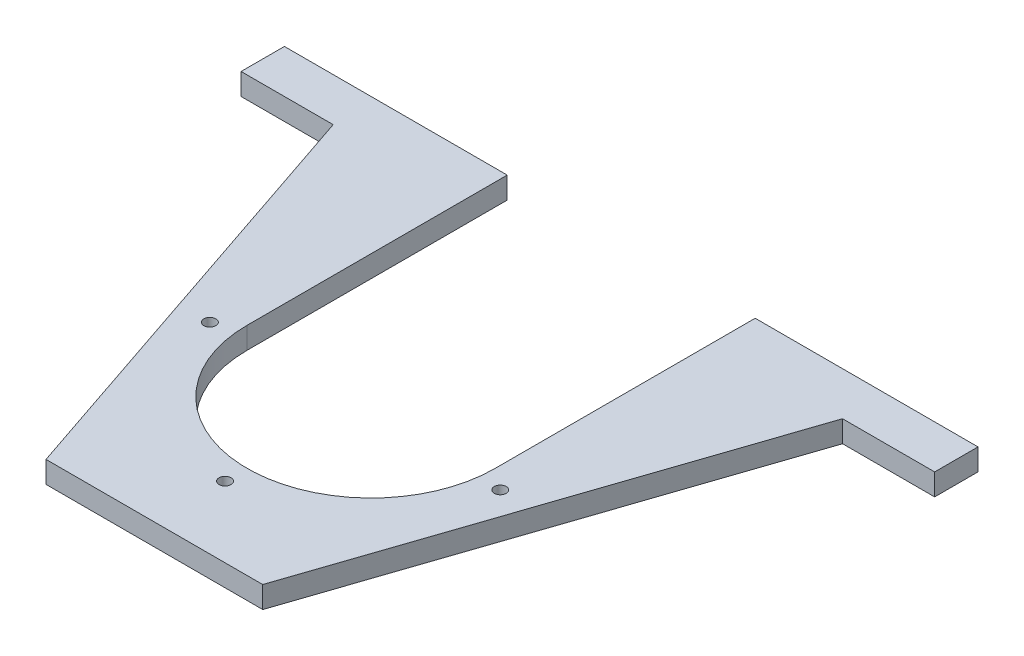
SolidWorks part; units mm, degrees
material "Pin"
ref_plane "Front" through (0, 0, 0) normal (0, 0, 1) x (1, 0, 0)
ref_plane "Top" through (0, 0, 0) normal (0, 1, 0) x (1, 0, 0)
ref_plane "Right" through (0, 0, 0) normal (1, 0, 0) x (0, 0, -1)
sketch "Esquisse1" plane through (0, 0, 0) normal (0, 1, 0) x (1, 0, 0)
  line L2 (-101.6, 139.7) -> (-101.6, 127)
  line L3 (-101.6, 127) -> (-74.6125, 127)
  line L4 (-74.6125, 127) -> (-31.75, 0)
  line L10 (0, 0) -> (0, 160.2728) construction
  line L12 (74.6125, 127) -> (31.75, 0)
  line L13 (101.6, 127) -> (74.6125, 127)
  line L14 (101.6, 139.7) -> (101.6, 127)
  line L18 (-101.6, 139.7) -> (101.6, 139.7)
  line L19 (-31.75, 0) -> (31.75, 0)
  point P2 (0, 0)
  point P6 (-88.1063, 127)
  dimension "D1" = 12.7
  dimension "D2" = 101.6
  dimension "D3" = 63.5
  dimension "D5" = 127
  dimension "D8" = 26.9875
extrude "Boss.-Extru.1" add sketch "Esquisse1" along normal blind 6.35
sketch "Esquisse3" plane through (0, 6.35, 0) normal (0, 1, 0) x (1, 0, 0)
  line L1 (-31.75, 0) -> (31.75, 0) construction
  circle A0 centre (0, 63.5) radius 36.322
  dimension "D1" = 72.644
  dimension "D2" = 63.5
extrude "Enlèv. mat.-Extru.2" cut sketch "Esquisse3" against normal through all
sketch "Esquisse4" plane through (0, 6.35, 0) normal (0, 1, 0) x (1, 0, 0)
  line L1 (65.4949, 139.7) -> (23.1087, 139.7)
  line L3 (61.2087, 127) -> (23.1087, 127)
  line L4 (23.1087, 139.7) -> (23.1087, 127)
  line L5 (101.6, 139.7) -> (-101.6, 139.7) construction
  line L6 (61.2087, 127) -> (65.4949, 139.7)
  line L7 (31.75, 0) -> (74.6125, 127) construction
  dimension "D1" = 12.7
  dimension "D2" = 38.1
  dimension "D3" = 12.7
extrude "Enlèv. mat.-Extru.3" [suppressed] cut sketch "Esquisse4" against normal through all
sketch "Esquisse5" plane through (0, 6.35, 0) normal (0, 1, 0) x (1, 0, 0)
  line L0 (0, 123.444) -> (0, 132.8849)
  line L1 (0, 132.8849) -> (3.175, 132.8849)
  line L2 (3.175, 132.8849) -> (3.175, 123.3599)
  line L3 (3.175, 123.3599) -> (0, 123.444)
  line L4 (14.8109, 121.7492) -> (11.7133, 122.4512)
  line L5 (11.7133, 122.4512) -> (13.5551, 131.7106)
  line L6 (13.5551, 131.7106) -> (16.6691, 131.0912)
  line L7 (16.6691, 131.0912) -> (14.8109, 121.7492)
  line L8 (25.909, 117.8995) -> (23.0079, 119.1923)
  line L9 (23.0079, 119.1923) -> (26.6207, 127.9145)
  line L10 (26.6207, 127.9145) -> (29.5541, 126.6995)
  line L11 (29.5541, 126.6995) -> (25.909, 117.8995)
  line L12 (36.0428, 111.9587) -> (33.4496, 113.7926)
  line L13 (33.4496, 113.7926) -> (38.6947, 121.6423)
  line L14 (38.6947, 121.6423) -> (41.3346, 119.8784)
  line L15 (41.3346, 119.8784) -> (36.0428, 111.9587)
  line L16 (44.8229, 104.1549) -> (42.6373, 106.4595)
  line L17 (42.6373, 106.4595) -> (49.313, 113.1352)
  line L18 (49.313, 113.1352) -> (51.5581, 110.8901)
  line L19 (51.5581, 110.8901) -> (44.8229, 104.1549)
  line L20 (51.9118, 94.7882) -> (50.2179, 97.4749)
  line L21 (50.2179, 97.4749) -> (58.0677, 102.72)
  line L22 (58.0677, 102.72) -> (59.8316, 100.08)
  line L23 (59.8316, 100.08) -> (51.9118, 94.7882)
  line L108 (-47.6582, 98.7102) -> (-49.4921, 96.117)
  line L109 (-49.4921, 96.117) -> (-57.3419, 101.3621)
  line L110 (-57.3419, 101.3621) -> (-55.5779, 104.002)
  line L111 (-55.5779, 104.002) -> (-47.6582, 98.7102)
  line L112 (-39.8544, 107.4903) -> (-42.159, 105.3047)
  line L113 (-42.159, 105.3047) -> (-48.8347, 111.9804)
  line L114 (-48.8347, 111.9804) -> (-46.5896, 114.2255)
  line L115 (-46.5896, 114.2255) -> (-39.8544, 107.4903)
  line L116 (-30.4878, 114.5792) -> (-33.1744, 112.8853)
  line L117 (-33.1744, 112.8853) -> (-38.4195, 120.735)
  line L118 (-38.4195, 120.735) -> (-35.7796, 122.499)
  line L119 (-35.7796, 122.499) -> (-30.4878, 114.5792)
  line L120 (-19.9181, 119.7046) -> (-22.8836, 118.5673)
  line L121 (-22.8836, 118.5673) -> (-26.4964, 127.2895)
  line L122 (-26.4964, 127.2895) -> (-23.5631, 128.5046)
  line L123 (-23.5631, 128.5046) -> (-19.9181, 119.7046)
  line L124 (-8.5515, 122.6695) -> (-11.6819, 122.1326)
  line L125 (-11.6819, 122.1326) -> (-13.5238, 131.392)
  line L126 (-13.5238, 131.392) -> (-10.4098, 132.0114)
  line L127 (-10.4098, 132.0114) -> (-8.5515, 122.6695)
  line L128 (57.0372, 84.2185) -> (55.8999, 87.184) [skipped]
  line L129 (55.8999, 87.184) -> (64.6222, 90.7969) [skipped]
  line L130 (64.6222, 90.7969) -> (65.8372, 87.8636) [skipped]
  line L131 (65.8372, 87.8636) -> (57.0372, 84.2185) [skipped]
  line L132 (60.0021, 72.852) -> (59.4652, 75.9824) [skipped]
  line L133 (59.4652, 75.9824) -> (68.7247, 77.8242) [skipped]
  line L134 (68.7247, 77.8242) -> (69.3441, 74.7102) [skipped]
  line L135 (69.3441, 74.7102) -> (60.0021, 72.852) [skipped]
  line L136 (60.6925, 61.1255) -> (60.7766, 64.3005) [skipped]
  line L137 (60.7766, 64.3005) -> (70.2175, 64.3005) [skipped]
  line L138 (70.2175, 64.3005) -> (70.2175, 61.1255) [skipped]
  line L139 (70.2175, 61.1255) -> (60.6925, 61.1255) [skipped]
  line L140 (59.0819, 49.4896) -> (59.7838, 52.5872) [skipped]
  line L141 (59.7838, 52.5872) -> (69.0433, 50.7453) [skipped]
  line L142 (69.0433, 50.7453) -> (68.4238, 47.6313) [skipped]
  line L143 (68.4238, 47.6313) -> (59.0819, 49.4896) [skipped]
  line L144 (55.2321, 38.3915) -> (56.5249, 41.2926) [skipped]
  line L145 (56.5249, 41.2926) -> (65.2471, 37.6797) [skipped]
  line L146 (65.2471, 37.6797) -> (64.0321, 34.7464) [skipped]
  line L147 (64.0321, 34.7464) -> (55.2321, 38.3915) [skipped]
  line L148 (49.2913, 28.2577) -> (51.1252, 30.8508) [skipped]
  line L149 (51.1252, 30.8508) -> (58.975, 25.6058) [skipped]
  line L150 (58.975, 25.6058) -> (57.211, 22.9659) [skipped]
  line L151 (57.211, 22.9659) -> (49.2913, 28.2577) [skipped]
  line L152 (41.4875, 19.4776) -> (43.7921, 21.6631) [skipped]
  line L153 (43.7921, 21.6631) -> (50.4678, 14.9875) [skipped]
  line L154 (50.4678, 14.9875) -> (48.2227, 12.7424) [skipped]
  line L155 (48.2227, 12.7424) -> (41.4875, 19.4776) [skipped]
  line L156 (32.1208, 12.3886) -> (34.8075, 14.0826) [skipped]
  line L157 (34.8075, 14.0826) -> (40.0526, 6.2328) [skipped]
  line L158 (40.0526, 6.2328) -> (37.4127, 4.4689) [skipped]
  line L159 (37.4127, 4.4689) -> (32.1208, 12.3886) [skipped]
  line L160 (21.5511, 7.2633) -> (24.5167, 8.4005) [skipped]
  line L161 (24.5167, 8.4005) -> (28.1295, -0.3217) [skipped]
  line L162 (28.1295, -0.3217) -> (25.1962, -1.5367) [skipped]
  line L163 (25.1962, -1.5367) -> (21.5511, 7.2633) [skipped]
  line L164 (10.1846, 4.2984) -> (13.315, 4.8353) [skipped]
  line L165 (-1.5419, 3.608) -> (1.6331, 3.5239) [skipped]
  line L166 (-13.1778, 5.2186) -> (-10.0802, 4.5167) [skipped]
  line L167 (-24.2759, 9.0683) -> (-21.3748, 7.7756) [skipped]
  line L168 (-21.3748, 7.7756) -> (-24.9876, -0.9466) [skipped]
  line L169 (-24.9876, -0.9466) -> (-27.921, 0.2684) [skipped]
  line L170 (-27.921, 0.2684) -> (-24.2759, 9.0683) [skipped]
  line L171 (-34.4097, 15.0092) -> (-31.8165, 13.1753) [skipped]
  line L172 (-31.8165, 13.1753) -> (-37.0616, 5.3255) [skipped]
  line L173 (-37.0616, 5.3255) -> (-39.7015, 7.0895) [skipped]
  line L174 (-39.7015, 7.0895) -> (-34.4097, 15.0092) [skipped]
  line L175 (-43.1898, 22.8129) -> (-41.0042, 20.5084) [skipped]
  line L176 (-41.0042, 20.5084) -> (-47.6799, 13.8327) [skipped]
  line L177 (-47.6799, 13.8327) -> (-49.925, 16.0777) [skipped]
  line L178 (-49.925, 16.0777) -> (-43.1898, 22.8129) [skipped]
  line L179 (-50.2787, 32.1796) -> (-48.5848, 29.493) [skipped]
  line L180 (-48.5848, 29.493) -> (-56.4346, 24.2479) [skipped]
  line L181 (-56.4346, 24.2479) -> (-58.1985, 26.8878) [skipped]
  line L182 (-58.1985, 26.8878) -> (-50.2787, 32.1796) [skipped]
  line L183 (-55.4041, 42.7493) -> (-54.2669, 39.7838) [skipped]
  line L184 (-54.2669, 39.7838) -> (-62.9891, 36.171) [skipped]
  line L185 (-62.9891, 36.171) -> (-64.2041, 39.1043) [skipped]
  line L186 (-64.2041, 39.1043) -> (-55.4041, 42.7493) [skipped]
  line L187 (-58.369, 54.1159) -> (-57.8321, 50.9854) [skipped]
  line L188 (-57.8321, 50.9854) -> (-67.0916, 49.1436) [skipped]
  line L189 (-67.0916, 49.1436) -> (-67.711, 52.2576) [skipped]
  line L190 (-67.711, 52.2576) -> (-58.369, 54.1159) [skipped]
  line L191 (-59.0594, 65.8424) -> (-59.1435, 62.6674) [skipped]
  line L192 (-59.1435, 62.6674) -> (-68.5844, 62.6674) [skipped]
  line L193 (-68.5844, 62.6674) -> (-68.5844, 65.8424) [skipped]
  line L194 (-68.5844, 65.8424) -> (-59.0594, 65.8424) [skipped]
  line L195 (-57.4488, 77.4783) -> (-58.1507, 74.3807) [skipped]
  line L196 (-58.1507, 74.3807) -> (-67.4102, 76.2225) [skipped]
  line L197 (-67.4102, 76.2225) -> (-66.7907, 79.3365) [skipped]
  line L198 (-66.7907, 79.3365) -> (-57.4488, 77.4783) [skipped]
  line L199 (-53.5991, 88.5764) -> (-54.8918, 85.6753) [skipped]
  line L200 (-54.8918, 85.6753) -> (-63.614, 89.2881) [skipped]
  line L201 (-63.614, 89.2881) -> (-62.399, 92.2214) [skipped]
  line L202 (-62.399, 92.2214) -> (-53.5991, 88.5764) [skipped]
  line L203 (13.315, 4.8353) -> (15.1569, -4.4242) [skipped]
  line L204 (15.1569, -4.4242) -> (12.0429, -5.0436) [skipped]
  line L205 (12.0429, -5.0436) -> (10.1846, 4.2984) [skipped]
  line L206 (1.6331, 3.5239) -> (1.6331, -5.917) [skipped]
  line L207 (1.6331, -5.917) -> (-1.5419, -5.917) [skipped]
  line L208 (-1.5419, -5.917) -> (-1.5419, 3.608) [skipped]
  line L209 (-10.0802, 4.5167) -> (-11.922, -4.7428) [skipped]
  line L210 (-11.922, -4.7428) -> (-15.036, -4.1234) [skipped]
  line L211 (-15.036, -4.1234) -> (-13.1778, 5.2186) [skipped]
  circle A1 centre (0, 63.5) radius 59.944 construction
  dimension "D1" = 119.888
  dimension "D2" = 3.175
  dimension "D3" = 9.525
  dimension "D4" = 32
extrude "Enlèv. mat.-Extru.4" [suppressed] cut sketch "Esquisse5" against normal blind 6.35
sketch "Esquisse6" plane through (0, 6.35, 0) normal (0, 1, 0) x (1, 0, 0)
  line L0 (-36.322, 63.5) -> (-36.322, 139.7)
  line L1 (101.6, 139.7) -> (-101.6, 139.7) construction
  line L2 (36.322, 63.5) -> (36.322, 139.7)
  line L3 (36.322, 139.7) -> (-36.322, 139.7)
  circle A0 centre (0, 63.5) radius 36.322 construction
  arc A1 (36.322, 63.5) -> (-36.322, 63.5) centre (0, 63.5) ccw
extrude "Enlèv. mat.-Extru.5" cut sketch "Esquisse6" against normal blind 6.35
sketch "Esquisse7" plane through (0, 6.35, 0) normal (0, 1, 0) x (1, 0, 0)
  line L0 (-36.322, 63.5) -> (36.322, 63.5) construction
  circle A0 centre (0, 63.5) radius 42.799 construction
  circle A1 centre (0, 20.701) radius 1.75
  circle A3 centre (42.5403, 58.801) radius 1.75
  circle A4 centre (-42.5403, 58.801) radius 1.75
  point P12 (0, 0)
  dimension "D1" = 85.598
  dimension "D2" = 3.5
  dimension "D3" = 38.1
extrude "Enlèv. mat.-Extru.6" cut sketch "Esquisse7" against normal blind 6.35
